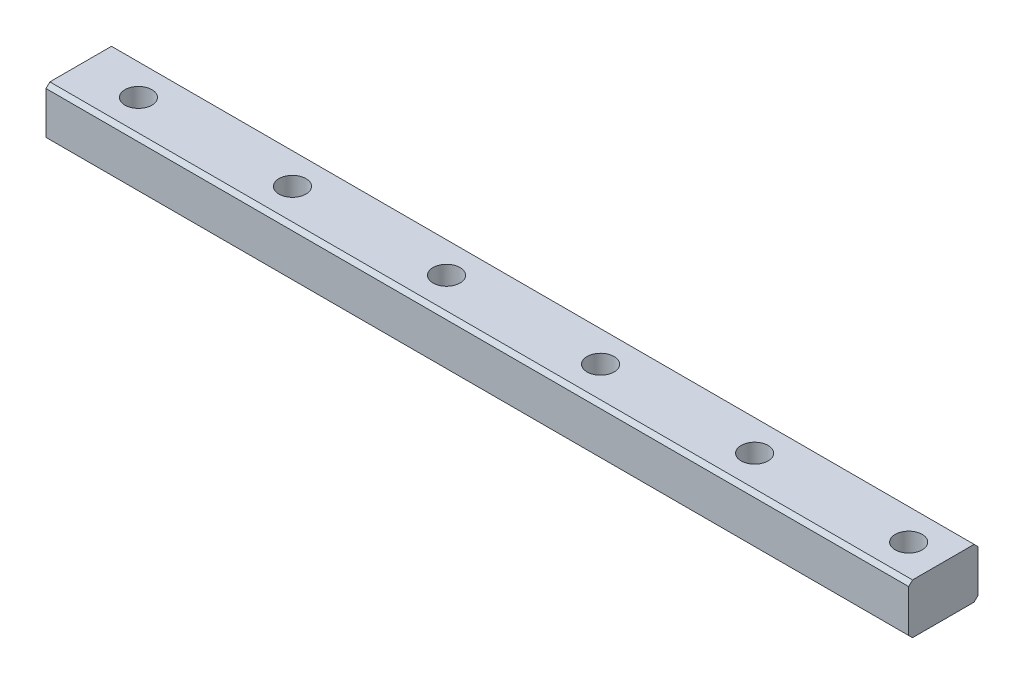
SolidWorks part; units mm, degrees
material "铸造合金钢"
ref_plane "前视基准面" through (0, 0, 0) normal (0, 0, 1) x (1, 0, 0)
ref_plane "上视基准面" through (0, 0, 0) normal (0, 1, 0) x (1, 0, 0)
ref_plane "右视基准面" through (0, 0, 0) normal (1, 0, 0) x (0, 0, -1)
sketch "草图1" plane through (0, 0, 0) normal (1, 0, 0) x (0, 0, -1)
  line L1 (4.5, -3.25) -> (-4.5, -3.25)
  line L2 (4.5, -3.25) -> (4.5, 3.25)
  line L3 (4.5, 3.25) -> (-4.5, 3.25)
  line L4 (-4.5, -3.25) -> (-4.5, 3.25)
  line L5 (4.5, -3.25) -> (-4.5, 3.25) construction
  line L6 (4.5, 3.25) -> (-4.5, -3.25) construction
  point P0 (0, 0)
  dimension "D1" = 9
  dimension "D2" = 6.5
extrude "拉伸1" add sketch "草图1" along normal blind 112
sketch "草图2" plane through (0, -3.25, 0) normal (0, -1, 0) x (1, 0, 0)
  line L0 (0, 4.5) -> (0, -4.5) construction
  circle A0 centre (7.5, 0) radius 1.75
  circle A1 centre (167.5, 0) radius 1.75
  circle A2 centre (187.5, 0) radius 1.75
  circle A3 centre (207.5, 0) radius 1.75
  circle A4 centre (227.5, 0) radius 1.75
  circle A5 centre (247.5, 0) radius 1.75
  circle A6 centre (267.5, 0) radius 1.75
  circle A7 centre (287.5, 0) radius 1.75
  circle A50 centre (27.5, 0) radius 1.75
  circle A51 centre (47.5, 0) radius 1.75
  circle A52 centre (67.5, 0) radius 1.75
  circle A53 centre (87.5, 0) radius 1.75
  circle A54 centre (107.5, 0) radius 1.75
  circle A55 centre (127.5, 0) radius 1.75
  circle A56 centre (147.5, 0) radius 1.75
  dimension "D1" = 7.5
  dimension "D2" = 3.5
  dimension "D3" = 15
extrude "拉伸2" cut sketch "草图2" against normal blind 8
sketch "草图3" plane through (0, -3.25, 0) normal (0, -1, 0) x (1, 0, 0)
  circle A0 centre (7.5, 0) radius 3
  circle A1 centre (7.5, 0) radius 1.75 construction
  circle A2 centre (167.5, 0) radius 3
  circle A3 centre (187.5, 0) radius 3
  circle A4 centre (207.5, 0) radius 3
  circle A5 centre (227.5, 0) radius 3
  circle A6 centre (247.5, 0) radius 3
  circle A7 centre (267.5, 0) radius 3
  circle A8 centre (287.5, 0) radius 3
  circle A51 centre (27.5, 0) radius 3
  circle A52 centre (47.5, 0) radius 3
  circle A53 centre (67.5, 0) radius 3
  circle A54 centre (87.5, 0) radius 3
  circle A55 centre (107.5, 0) radius 3
  circle A56 centre (127.5, 0) radius 3
  circle A57 centre (147.5, 0) radius 3
  dimension "D1" = 6
  dimension "D2" = 15
extrude "拉伸3" cut sketch "草图3" against normal blind 3.5
chamfer "倒角1" distance 0.5 angle 45 4 edges at (56, -3.25, 4.5) (56, 3.25, 4.5) (56, 3.25, -4.5) (56, -3.25, -4.5)
